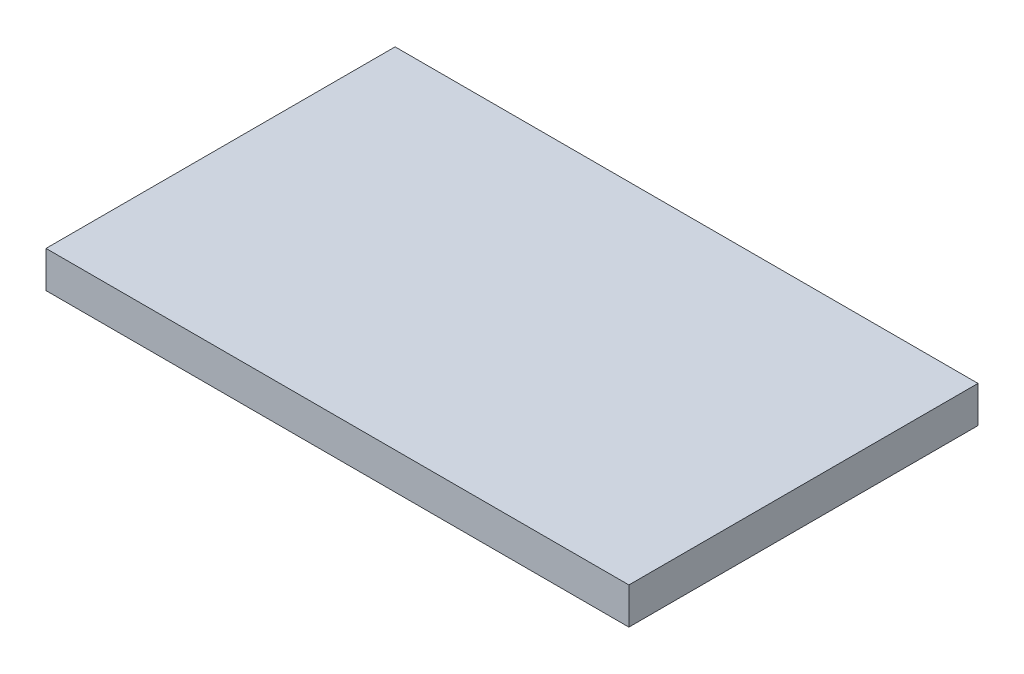
SolidWorks part; units mm, degrees
ref_plane "Front Plane" through (0, 0, 0) normal (0, 0, 1) x (1, 0, 0)
ref_plane "Top Plane" through (0, 0, 0) normal (0, 1, 0) x (1, 0, 0)
ref_plane "Right Plane" through (0, 0, 0) normal (1, 0, 0) x (0, 0, -1)
sketch "Sketch1" plane through (0, 0, 0) normal (0, 1, 0) x (1, 0, 0)
  line L1 (0, 0) -> (40.4939, 0)
  line L2 (0, 0) -> (0, 24.2514)
  line L3 (0, 24.2514) -> (40.4939, 24.2514)
  line L4 (40.4939, 0) -> (40.4939, 24.2514)
extrude "Boss-Extrude1" add sketch "Sketch1" along normal blind 2.54
